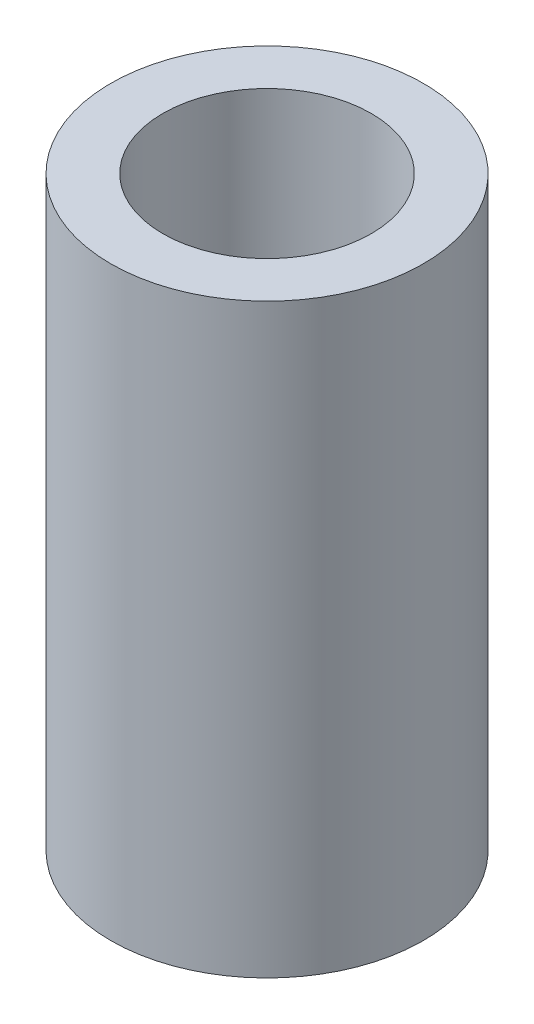
SolidWorks part; units mm, degrees
ref_plane "Спереди" through (0, 0, 0) normal (0, 0, 1) x (1, 0, 0)
ref_plane "Сверху" through (0, 0, 0) normal (0, 1, 0) x (1, 0, 0)
ref_plane "Справа" through (0, 0, 0) normal (1, 0, 0) x (0, 0, -1)
sketch "Эскиз1" plane through (0, 0, 0) normal (0, 1, 0) x (1, 0, 0)
  circle A0 centre (0, 0) radius 1.6
  circle A1 centre (0, 0) radius 2.4
  dimension "D1" = 3.2
  dimension "D2" = 4.8
extrude "Бобышка-Вытянуть1" add sketch "Эскиз1" along normal blind 9
